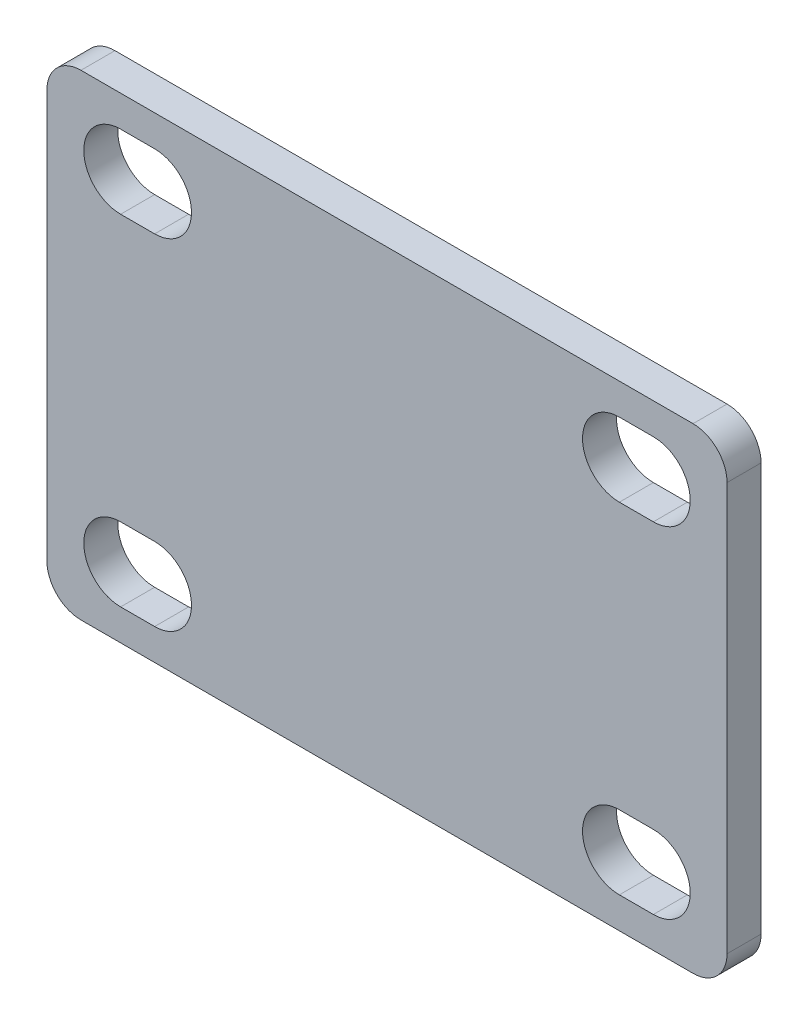
SolidWorks part; units mm, degrees
ref_plane "前视基准面" through (0, 0, 0) normal (0, 0, 1) x (1, 0, 0)
ref_plane "上视基准面" through (0, 0, 0) normal (0, 1, 0) x (1, 0, 0)
ref_plane "右视基准面" through (0, 0, 0) normal (1, 0, 0) x (0, 0, -1)
other "Configuration Table"
sketch "草图1" plane through (0, 0, 0) normal (0, 0, 1) x (1, 0, 0)
  line L1 (-30, 21) -> (30, 21)
  line L2 (-30, 21) -> (-30, -21)
  line L3 (-30, -21) -> (30, -21)
  line L4 (30, 21) -> (30, -21)
  dimension "D1" = 42
  dimension "D2" = 60
  dimension "D3" = 21
  dimension "D4" = 30
extrude "凸台-拉伸1" add sketch "草图1" along normal blind 3
sketch "草图2" plane through (0, 0, 3) normal (0, 0, 1) x (1, 0, 0)
  line L0 (0, 0) -> (50000, 0) construction
  line L1 (-23.5, 15) -> (-20.5, 15) construction
  line L2 (-23.5, 18.25) -> (-20.5, 18.25)
  line L3 (-23.5, 11.75) -> (-20.5, 11.75)
  line L4 (20.5, 15) -> (23.5, 15) construction
  line L5 (20.5, 18.25) -> (23.5, 18.25)
  line L6 (20.5, 11.75) -> (23.5, 11.75)
  line L7 (30, 21) -> (-30, 21) construction
  line L8 (20.5, -15) -> (23.5, -15) construction
  line L9 (20.5, -18.25) -> (23.5, -18.25)
  line L10 (20.5, -11.75) -> (23.5, -11.75)
  line L11 (-23.5, -15) -> (-20.5, -15) construction
  line L12 (-23.5, -18.25) -> (-20.5, -18.25)
  line L13 (-23.5, -11.75) -> (-20.5, -11.75)
  arc A0 (-23.5, 18.25) -> (-23.5, 11.75) centre (-23.5, 15) ccw
  arc A1 (-20.5, 11.75) -> (-20.5, 18.25) centre (-20.5, 15) ccw
  arc A2 (20.5, 18.25) -> (20.5, 11.75) centre (20.5, 15) ccw
  arc A3 (23.5, 11.75) -> (23.5, 18.25) centre (23.5, 15) ccw
  arc A4 (20.5, -18.25) -> (20.5, -11.75) centre (20.5, -15) cw
  arc A5 (23.5, -11.75) -> (23.5, -18.25) centre (23.5, -15) cw
  arc A6 (-23.5, -18.25) -> (-23.5, -11.75) centre (-23.5, -15) cw
  arc A7 (-20.5, -11.75) -> (-20.5, -18.25) centre (-20.5, -15) cw
  point P5 (-22, 15)
  point P10 (22, 15)
  point P17 (25.0939, 15.1353)
  point P20 (0, 21)
  point P23 (22, -15)
  point P30 (-22, -15)
  dimension "D2" = 3.25
  dimension "D3" = 3
  dimension "D1" = 44
  dimension "D4" = 3
  dimension "D5" = 6
  dimension "D6" = 22
extrude "切除-拉伸1" cut sketch "草图2" against normal blind 3
fillet "圆角1" radius 3 4 edges at (-30, 21, 1.5) (-30, -21, 1.5) (30, -21, 1.5) (30, 21, 1.5)
